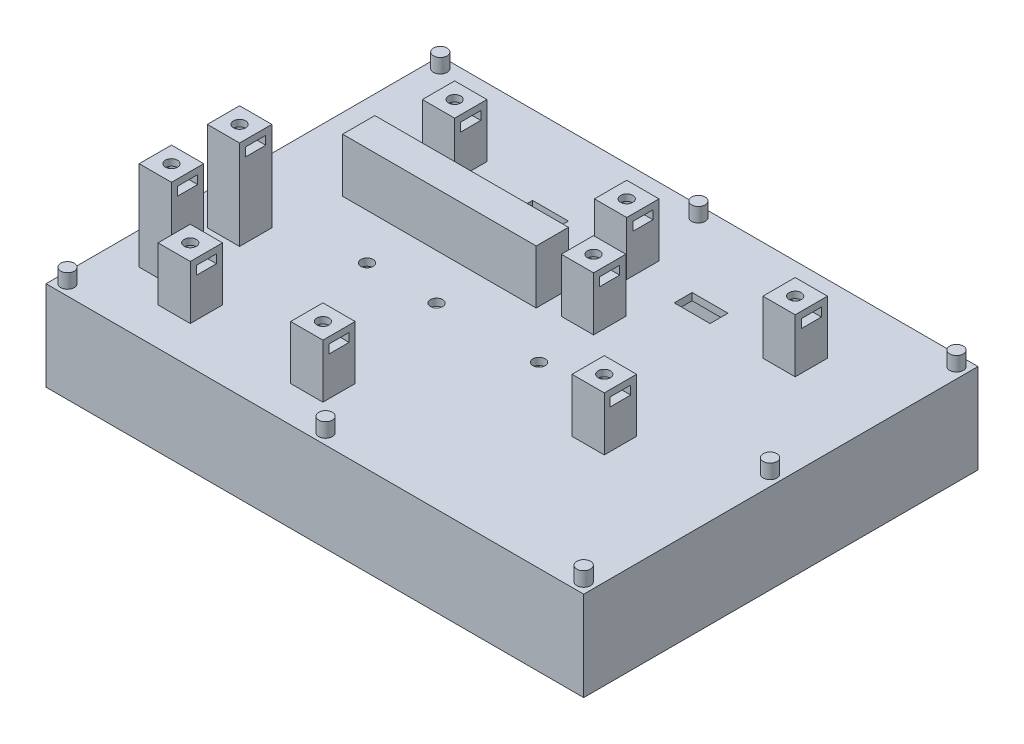
SolidWorks part; units mm, degrees
ref_plane "Front Plane" through (0, 0, 0) normal (0, 0, 1) x (1, 0, 0)
ref_plane "Top Plane" through (0, 0, 0) normal (0, 1, 0) x (1, 0, 0)
ref_plane "Right Plane" through (0, 0, 0) normal (1, 0, 0) x (0, 0, -1)
sketch "Sketch1" plane through (0, 0, 0) normal (0, 1, 0) x (1, 0, 0)
  line L1 (0, 0) -> (150, 0)
  line L2 (0, 0) -> (0, 110)
  line L3 (0, 110) -> (150, 110)
  line L4 (150, 0) -> (150, 110)
  dimension "D1" = 150
  dimension "D2" = 110
extrude "Boss-Extrude1" add sketch "Sketch1" along normal blind 25
sketch "PCB" plane through (0, 25, 0) normal (0, 1, 0) x (1, 0, 0)
  line L1 (20.25, 72) -> (129.75, 72)
  line L2 (20.25, 72) -> (20.25, 9.5)
  line L3 (20.25, 9.5) -> (129.75, 9.5)
  line L4 (129.75, 72) -> (129.75, 9.5)
  line L5 (0, 0) -> (150, 0) construction
  line L6 (150, 0) -> (150, 110) construction
  line L7 (0, 110) -> (0, 0) construction
  line L8 (150, 110) -> (0, 110) construction
  line L9 (24.5, 100.5) -> (125.5, 100.5)
  line L10 (24.5, 100.5) -> (24.5, 74)
  line L11 (24.5, 74) -> (125.5, 74)
  line L12 (125.5, 100.5) -> (125.5, 74)
  point P16 (75, 72)
  point P17 (75, 74)
  dimension "D1" = 109.5
  dimension "D2" = 62.5
  dimension "D3" = 9.5
  dimension "D4" = 20.25
  dimension "D5" = 20.25
  dimension "D6" = 26.5
  dimension "D7" = 2
  dimension "D8" = 9.5
  dimension "D9" = 101
sketch "Sketch10" plane through (0, 0, 0) normal (0, -1, 0) x (1, 0, 0)
  line L0 (0, 0) -> (150, 0) construction
  line L1 (117.75, -90) -> (32.25, -90)
  line L2 (117.75, -90) -> (117.75, -12)
  line L3 (117.75, -12) -> (32.25, -12)
  line L4 (32.25, -90) -> (32.25, -12)
  line L6 (150, -110) -> (0, -110) construction
  line L7 (150, 0) -> (150, -110) construction
  dimension "D1" = 85.5
  dimension "D2" = 78
  dimension "D3" = 20
  dimension "D4" = 32.25
  dimension "D5" = 12
sketch "Sketch27" plane through (0, 25, 0) normal (0, 1, 0) x (1, 0, 0)
  line L0 (150, 110) -> (0, 110) construction
  line L1 (0, 110) -> (0, 0) construction
  line L2 (0, 0) -> (150, 0) construction
  line L3 (150, 0) -> (150, 110) construction
  circle A0 centre (3, 107) radius 1.9
  circle A1 centre (75, 107) radius 1.9
  circle A2 centre (147, 107) radius 1.9
  circle A3 centre (147, 55) radius 1.9
  circle A4 centre (147, 3) radius 1.9
  circle A5 centre (75, 3) radius 1.9
  circle A6 centre (3, 3) radius 1.9
  circle A7 centre (3, 55) radius 1.9
  point P21 (0, 55)
  point P26 (75, 0)
  point P32 (150, 55)
  point P35 (75, 110)
  dimension "D1" = 3.8
  dimension "D4" = 3.8
  dimension "D5" = 3.8
  dimension "D6" = 3.8
  dimension "D7" = 3.8
  dimension "D8" = 3.8
  dimension "D9" = 3.8
  dimension "D10" = 3.8
  dimension "D2" = 3
  dimension "D3" = 3
  dimension "D11" = 3
  dimension "D12" = 3
  dimension "D13" = 3
  dimension "D14" = 3
extrude "Connectors" add sketch "Sketch27" along normal blind 4
sketch "Sketch31" plane through (0, 25, 0) normal (0, 1, 0) x (1, 0, 0)
  line L0 (24.5, 100.5) -> (24.5, 74) construction
  line L1 (118, 91) -> (127, 91)
  line L2 (118, 91) -> (118, 82)
  line L3 (129.75, 41) -> (114.75, 41) construction
  line L6 (20.25, 72) -> (20.25, 9.5) construction
  line L7 (20.25, 15) -> (25.25, 15) construction
  line L9 (84.25, 72) -> (84.25, 68.5) construction
  line L10 (129.75, 72) -> (129.75, 9.5) construction
  line L11 (20.25, 72) -> (129.75, 72) construction
  line L12 (118, 82) -> (127, 82)
  line L13 (20.25, 9.5) -> (129.75, 9.5) construction
  line L14 (127, 91) -> (127, 82)
  line L15 (20.75, 19.5) -> (29.75, 19.5)
  line L16 (20.75, 19.5) -> (20.75, 10.5)
  line L17 (20.75, 10.5) -> (29.75, 10.5)
  line L18 (29.75, 19.5) -> (29.75, 10.5)
  line L19 (20.75, 19.5) -> (29.75, 10.5) construction
  line L20 (20.75, 10.5) -> (29.75, 19.5) construction
  line L21 (58.25, 19) -> (67.25, 19)
  line L22 (58.25, 19) -> (58.25, 10)
  line L23 (58.25, 10) -> (67.25, 10)
  line L24 (67.25, 19) -> (67.25, 10)
  line L25 (58.25, 19) -> (67.25, 10) construction
  line L26 (58.25, 10) -> (67.25, 19) construction
  line L27 (110.25, 45.5) -> (119.25, 45.5)
  line L28 (110.25, 45.5) -> (110.25, 36.5)
  line L29 (110.25, 36.5) -> (119.25, 36.5)
  line L30 (119.25, 45.5) -> (119.25, 36.5)
  line L31 (110.25, 45.5) -> (119.25, 36.5) construction
  line L32 (110.25, 36.5) -> (119.25, 45.5) construction
  line L33 (79.75, 73) -> (88.75, 73)
  line L34 (79.75, 73) -> (79.75, 64)
  line L35 (79.75, 64) -> (88.75, 64)
  line L36 (88.75, 73) -> (88.75, 64)
  line L37 (79.75, 73) -> (88.75, 64) construction
  line L38 (79.75, 64) -> (88.75, 73) construction
  line L43 (118, 91) -> (127, 82) construction
  line L44 (118, 82) -> (127, 91) construction
  line L49 (71, 91) -> (80, 91)
  line L50 (71, 91) -> (71, 82)
  line L51 (71, 82) -> (80, 82)
  line L52 (80, 91) -> (80, 82)
  line L53 (71, 91) -> (80, 82) construction
  line L54 (71, 82) -> (80, 91) construction
  line L55 (23, 91) -> (32, 91)
  line L56 (23, 91) -> (23, 82)
  line L57 (23, 82) -> (32, 82)
  line L58 (32, 91) -> (32, 82)
  line L59 (23, 91) -> (32, 82) construction
  line L60 (23, 82) -> (32, 91) construction
  line L61 (24.5, 74) -> (125.5, 74) construction
  line L62 (125.5, 100.5) -> (125.5, 74) construction
  line L63 (150, 110) -> (0, 110) construction
  point P0 (122.5, 86.5)
  point P8 (75.5, 86.5)
  point P40 (27.5, 86.5)
  point P48 (62.75, 14.5)
  dimension "D3" = 5
  dimension "D4" = 37.5
  dimension "D5" = 5.5
  dimension "D6" = 45.5
  dimension "D7" = 3.5
  dimension "D8" = 15
  dimension "D9" = 31.5
  dimension "D10" = 9
  dimension "D11" = 9
  dimension "D12" = 9
  dimension "D13" = 9
  dimension "D14" = 9
  dimension "D15" = 9
  dimension "D16" = 9
  dimension "D17" = 9
  dimension "D18" = 9
  dimension "D19" = 9
  dimension "D20" = 9
  dimension "D21" = 9
  dimension "D22" = 5
  dimension "D23" = 9
  dimension "D24" = 9
  dimension "D25" = 3
  dimension "D26" = 12.5
  dimension "D27" = 12.5
  dimension "D28" = 50
  dimension "D29" = 3
  dimension "D30" = 12.5
  dimension "D31" = 23.5
extrude "Pillars" add sketch "Sketch31" along normal blind 15
hole_wizard "M3 Clearance Hole3" positions "3DSketch1" profile "Sketch32" hole size "M3" standard "ANSI Metric"
sketch3d "3DSketch1"
  line L0 (58.25, 40, -10) -> (67.25, 40, -10) construction
  point P4 (84.25, 40, -68.5)
  point P6 (114.75, 40, -41)
  point P8 (62.75, 40, -14.5)
  point P10 (25.25, 40, -15)
  point P56 (27.5, 40, -86.5)
  point P58 (75.5, 40, -86.5)
  point P60 (122.5, 40, -86.5)
  dimension "D1" = 4.5
sketch "Sketch32" plane through (84.25, 40, -68.5) normal (1, 0, 0) x (0, 0, 1)
  line L0 (0, 0) -> (0, 6.0215)
  line L1 (0, 6.0215) -> (1.7, 5)
  line L2 (1.7, 5) -> (1.7, 0)
  line L5 (1.7, 0) -> (0, 0)
  line L10 (0, 6.0215) -> (-1.7, 5) construction
  line L11 (0, -6.35) -> (0, 107.95) construction
  dimension "Hole Dia." = 3.4
  dimension "Hole Depth" = 5
  dimension "Drill Angle" = 118
sketch "Sketch33" plane through (119.25, 0, 0) normal (1, 0, 0) x (0, 0, -1)
  line L0 (36.5, 40) -> (45.5, 40) construction
  line L1 (38.15, 38.2) -> (43.85, 38.2)
  line L2 (38.15, 38.2) -> (38.15, 35.8)
  line L3 (38.15, 35.8) -> (43.85, 35.8)
  line L4 (43.85, 38.2) -> (43.85, 35.8)
  line L5 (38.15, 38.2) -> (43.85, 35.8) construction
  line L6 (38.15, 35.8) -> (43.85, 38.2) construction
  point P0 (41, 37)
  point P8 (41, 40)
  dimension "D1" = 5.7
  dimension "D2" = 2.4
  dimension "D3" = 1.8
extrude "Nut1" cut sketch "Sketch33" against normal blind 10
sketch "Sketch34" plane through (88.75, 0, 0) normal (1, 0, 0) x (0, 0, -1)
  line L0 (64, 40) -> (73, 40) construction
  line L1 (65.7, 38.2) -> (71.3, 38.2)
  line L2 (65.7, 38.2) -> (65.7, 35.8)
  line L3 (65.7, 35.8) -> (71.3, 35.8)
  line L4 (71.3, 38.2) -> (71.3, 35.8)
  line L5 (65.7, 38.2) -> (71.3, 35.8) construction
  line L6 (65.7, 35.8) -> (71.3, 38.2) construction
  point P0 (68.5, 37)
  point P8 (68.5, 40)
  dimension "D1" = 1.8
  dimension "D2" = 2.4
  dimension "D3" = 5.6
extrude "Nut2" cut sketch "Sketch34" against normal blind 10
sketch "Sketch37" plane through (67.25, 0, 0) normal (1, 0, 0) x (0, 0, -1)
  line L0 (10, 40) -> (19, 40) construction
  line L1 (11.7, 38.2) -> (17.3, 38.2)
  line L2 (11.7, 38.2) -> (11.7, 35.8)
  line L3 (11.7, 35.8) -> (17.3, 35.8)
  line L4 (17.3, 38.2) -> (17.3, 35.8)
  line L5 (11.7, 38.2) -> (17.3, 35.8) construction
  line L6 (11.7, 35.8) -> (17.3, 38.2) construction
  point P0 (14.5, 37)
  point P8 (14.5, 40)
  dimension "D1" = 2.4
  dimension "D2" = 5.6
  dimension "D3" = 1.8
extrude "Nut5" cut sketch "Sketch37" against normal blind 10
sketch "Sketch38" plane through (29.75, 0, 0) normal (1, 0, 0) x (0, 0, -1)
  line L0 (10.5, 40) -> (19.5, 40) construction
  line L1 (12.2, 38.2) -> (17.8, 38.2)
  line L2 (12.2, 38.2) -> (12.2, 35.8)
  line L3 (12.2, 35.8) -> (17.8, 35.8)
  line L4 (17.8, 38.2) -> (17.8, 35.8)
  line L5 (12.2, 38.2) -> (17.8, 35.8) construction
  line L6 (12.2, 35.8) -> (17.8, 38.2) construction
  point P0 (15, 37)
  point P8 (15, 40)
  dimension "D1" = 2.4
  dimension "D2" = 1.8
  dimension "D3" = 5.6
extrude "Nut6" cut sketch "Sketch38" against normal blind 10 contours L1 L4 L3 L2
extrude "Battery holder" cut sketch "Sketch10" against normal blind 23
sketch "Sketch39" plane through (0, 23, 0) normal (0, -1, 0) x (1, 0, 0)
  line L0 (117.75, -12) -> (32.25, -12) construction
  line L1 (76.75, -76) -> (69.75, -76)
  line L2 (76.75, -76) -> (76.75, -16)
  line L3 (76.75, -16) -> (69.75, -16)
  line L4 (69.75, -76) -> (69.75, -16)
  line L5 (76.75, -76) -> (69.75, -16) construction
  line L6 (76.75, -16) -> (69.75, -76) construction
  line L7 (32.25, -12) -> (32.25, -90) construction
  line L8 (117.75, -90) -> (117.75, -12) construction
  point P0 (73.25, -46)
  dimension "D1" = 41
  dimension "D2" = 60
  dimension "D3" = 34
  dimension "D4" = 41
extrude "Divider" add sketch "Sketch39" along normal blind 10
hole_wizard "M3 Clearance Hole4" positions "3DSketch2" profile "Sketch40" hole size "M3" standard "ANSI Metric"
sketch3d "3DSketch2"
  line L0 (117.75, 23, -90) -> (117.75, 23, -12) construction
  line L2 (117.75, 23, -12) -> (32.25, 23, -12) construction
  line L4 (69.75, 23, -16) -> (69.75, 23, -76) construction
  point P0 (107.15, 23, -49.8)
  point P2 (87.75, 23, -49.8)
  point P4 (59.15, 23, -49.8)
  point P6 (39.75, 23, -49.8)
  dimension "D1" = 19.4
  dimension "D2" = 10.6
  dimension "D3" = 37.8
  dimension "D4" = 10.6
  dimension "D5" = 19.4
sketch "Sketch40" plane through (107.15, 23, -49.8) normal (1, 0, 0) x (0, 0, -1)
  line L0 (0, 0) -> (0, 6.0215)
  line L1 (0, 6.0215) -> (1.7, 5)
  line L2 (1.7, 5) -> (1.7, 0)
  line L5 (1.7, 0) -> (0, 0)
  line L10 (0, 6.0215) -> (-1.7, 5) construction
  line L11 (0, -6.35) -> (0, 107.95) construction
  dimension "Hole Dia." = 3.4
  dimension "Hole Depth" = 5
  dimension "Drill Angle" = 118
sketch "Sketch41" plane through (0, 23, 0) normal (0, -1, 0) x (1, 0, 0)
  line L0 (117.75, -90) -> (117.75, -12) construction
  line L1 (102.25, -88) -> (92.25, -88)
  line L2 (102.25, -88) -> (102.25, -83)
  line L3 (102.25, -83) -> (92.25, -83)
  line L4 (92.25, -88) -> (92.25, -83)
  line L5 (102.25, -88) -> (92.25, -83) construction
  line L6 (102.25, -83) -> (92.25, -88) construction
  line L7 (57.75, -88) -> (47.75, -88)
  line L8 (57.75, -88) -> (57.75, -83)
  line L9 (57.75, -83) -> (47.75, -83)
  line L10 (47.75, -88) -> (47.75, -83)
  line L11 (57.75, -88) -> (47.75, -83) construction
  line L12 (57.75, -83) -> (47.75, -88) construction
  line L13 (32.25, -12) -> (32.25, -90) construction
  line L15 (117.75, -12) -> (32.25, -12) construction
  point P0 (97.25, -85.5)
  point P5 (52.75, -85.5)
  dimension "D1" = 5
  dimension "D2" = 5
  dimension "D3" = 10
  dimension "D4" = 10
  dimension "D5" = 20.5
  dimension "D6" = 20.5
  dimension "D7" = 71
  dimension "D8" = 71
extrude "Battery wire" cut sketch "Sketch41" against normal blind 2
sketch "Sketch42" plane through (0, 0, 0) normal (0, -1, 0) x (1, 0, 0)
  line L0 (32.25, -90) -> (117.75, -90) construction
  line L1 (117.75, -90) -> (117.75, -12) construction
  line L2 (32.25, -12) -> (32.25, -90) construction
  line L3 (117.75, -12) -> (32.25, -12) construction
  circle A0 centre (119.25, -10.5) radius 2
  circle A1 centre (30.75, -10.5) radius 2
  circle A2 centre (30.75, -91.5) radius 2
  circle A3 centre (119.25, -91.5) radius 2
  dimension "D1" = 4
  dimension "D4" = 4
  dimension "D9" = 4
  dimension "D12" = 4
  dimension "D2" = 1.5
  dimension "D3" = 1.5
  dimension "D5" = 1.5
  dimension "D6" = 1.5
  dimension "D7" = 1.5
  dimension "D8" = 1.5
  dimension "D10" = 1.5
  dimension "D11" = 1.5
  dimension "D13" = 88.5
  dimension "D14" = 81
  dimension "D15" = 88.5
  dimension "D16" = 81
extrude "Connector bottom" cut sketch "Sketch42" against normal blind 5
sketch "Sketch43" plane through (0, 25, 0) normal (0, 1, 0) x (1, 0, 0)
  line L0 (20.25, 72) -> (129.75, 72) construction
  line L1 (20.25, 71.5) -> (74.25, 71.5)
  line L2 (20.25, 71.5) -> (20.25, 62.5)
  line L3 (20.25, 62.5) -> (74.25, 62.5)
  line L4 (74.25, 71.5) -> (74.25, 62.5)
  line L9 (20.25, 72) -> (20.25, 9.5) construction
  dimension "D1" = 9
  dimension "D2" = 54
  dimension "D3" = 0
  dimension "D4" = 0.5
extrude "PCB rest" add sketch "Sketch43" along normal blind 15
sketch "Sketch44" plane through (127, 0, 0) normal (1, 0, 0) x (0, 0, -1)
  line L0 (82, 40) -> (91, 40) construction
  line L1 (89.3, 38.2) -> (83.7, 38.2)
  line L2 (89.3, 38.2) -> (89.3, 35.8)
  line L3 (89.3, 35.8) -> (83.7, 35.8)
  line L4 (83.7, 38.2) -> (83.7, 35.8)
  line L5 (89.3, 38.2) -> (83.7, 35.8) construction
  line L6 (89.3, 35.8) -> (83.7, 38.2) construction
  point P0 (86.5, 37)
  point P7 (86.5, 38.2)
  point P8 (86.5, 40)
  dimension "D1" = 2.4
  dimension "D2" = 5.6
  dimension "D3" = 1.8
extrude "Nut3" cut sketch "Sketch44" against normal blind 10
sketch "Sketch45" plane through (80, 0, 0) normal (1, 0, 0) x (0, 0, -1)
  line L0 (82, 40) -> (91, 40) construction
  line L1 (89.3, 38.2) -> (83.7, 38.2)
  line L2 (89.3, 38.2) -> (89.3, 35.8)
  line L3 (89.3, 35.8) -> (83.7, 35.8)
  line L4 (83.7, 38.2) -> (83.7, 35.8)
  line L5 (89.3, 38.2) -> (83.7, 35.8) construction
  line L6 (89.3, 35.8) -> (83.7, 38.2) construction
  point P0 (86.5, 37)
  point P7 (86.5, 38.2)
  point P8 (86.5, 40)
  dimension "D1" = 5.6
  dimension "D2" = 2.4
  dimension "D3" = 1.8
extrude "Nut4" cut sketch "Sketch45" against normal blind 10
sketch "Sketch46" plane through (32, 0, 0) normal (1, 0, 0) x (0, 0, -1)
  line L0 (82, 40) -> (91, 40) construction
  line L1 (83.7, 38.2) -> (89.3, 38.2)
  line L2 (83.7, 38.2) -> (83.7, 35.8)
  line L3 (83.7, 35.8) -> (89.3, 35.8)
  line L4 (89.3, 38.2) -> (89.3, 35.8)
  line L5 (83.7, 38.2) -> (89.3, 35.8) construction
  line L6 (83.7, 35.8) -> (89.3, 38.2) construction
  point P0 (86.5, 37)
  point P9 (86.5, 38.2)
  point P10 (86.5, 40)
  dimension "D1" = 5.6
  dimension "D2" = 2.4
  dimension "D3" = 1.8
extrude "Nut7" cut sketch "Sketch46" against normal blind 10
sketch "PCBInput" plane through (0, 25, 0) normal (0, 1, 0) x (1, 0, 0)
  line L0 (3, 31) -> (23, 31)
  line L1 (3, 43) -> (23, 43)
  line L2 (3, 43) -> (3, 19)
  line L3 (3, 19) -> (23, 19)
  line L4 (23, 43) -> (23, 19)
  line L5 (3, 43) -> (23, 19) construction
  line L6 (3, 19) -> (23, 43) construction
  line L7 (0, 110) -> (0, 0) construction
  line L8 (13.5, 43) -> (13.5, 40.5) construction
  line L9 (13.5, 19) -> (13.5, 21.5) construction
  line L10 (0, 0) -> (150, 0) construction
  point P0 (13, 31)
  dimension "D1" = 24
  dimension "D2" = 20
  dimension "D3" = 3
  dimension "D4" = 2.5
  dimension "D5" = 2.5
  dimension "D6" = 10.5
  dimension "D7" = 10.5
  dimension "D8" = 19
sketch "Sketch48" plane through (0, 25, 0) normal (0, 1, 0) x (1, 0, 0)
  line L1 (9, 45) -> (18, 45)
  line L2 (9, 45) -> (9, 36)
  line L3 (9, 36) -> (18, 36)
  line L4 (18, 45) -> (18, 36)
  line L5 (9, 45) -> (18, 36) construction
  line L6 (9, 36) -> (18, 45) construction
  line L7 (9, 26) -> (18, 26)
  line L8 (9, 26) -> (9, 17)
  line L9 (9, 17) -> (18, 17)
  line L10 (18, 26) -> (18, 17)
  line L11 (9, 26) -> (18, 17) construction
  line L12 (9, 17) -> (18, 26) construction
  point P0 (13.5, 40.5)
  point P6 (13.5, 21.5)
  dimension "D1" = 9
  dimension "D2" = 9
  dimension "D3" = 9
  dimension "D4" = 9
extrude "PCBInput pillars" add sketch "Sketch48" along normal blind 25 contours L3 L4 L1 L2
sketch "Sketch49" plane through (9, 0, 0) normal (-1, 0, 0) x (0, 0, 1)
  line L0 (-26, 50) -> (-17, 50) construction
  line L1 (-24.3, 45.8) -> (-18.7, 45.8)
  line L2 (-24.3, 45.8) -> (-24.3, 48.2)
  line L3 (-24.3, 48.2) -> (-18.7, 48.2)
  line L4 (-18.7, 45.8) -> (-18.7, 48.2)
  line L5 (-24.3, 45.8) -> (-18.7, 48.2) construction
  line L6 (-24.3, 48.2) -> (-18.7, 45.8) construction
  point P0 (-21.5, 47)
  point P7 (-21.5, 50)
  point P8 (-21.5, 48.2)
  dimension "D1" = 2.4
  dimension "D2" = 5.6
  dimension "D3" = 1.8
extrude "Nut8" cut sketch "Sketch49" against normal up to next
sketch "Sketch50" plane through (9, 0, 0) normal (-1, 0, 0) x (0, 0, 1)
  line L1 (-43.3, 45.8) -> (-37.7, 45.8)
  line L2 (-43.3, 45.8) -> (-43.3, 48.2)
  line L3 (-43.3, 48.2) -> (-37.7, 48.2)
  line L4 (-37.7, 45.8) -> (-37.7, 48.2)
  line L5 (-43.3, 45.8) -> (-37.7, 48.2) construction
  line L6 (-43.3, 48.2) -> (-37.7, 45.8) construction
  line L7 (-45, 50) -> (-36, 50) construction
  point P0 (-40.5, 47)
  point P7 (-40.5, 48.2)
  point P8 (-40.5, 50)
  dimension "D1" = 2.4
  dimension "D2" = 5.6
  dimension "D3" = 1.8
extrude "Nut9" cut sketch "Sketch50" against normal up to next
hole_wizard "M3 Clearance Hole5" positions "3DSketch3" profile "Sketch51" hole size "M3" standard "ANSI Metric"
sketch3d "3DSketch3"
  point P0 (13.5, 50, -40.5)
  point P2 (13.5, 50, -21.5)
sketch "Sketch51" plane through (13.5, 50, -40.5) normal (1, 0, 0) x (0, 0, 1)
  line L0 (0, 0) -> (0, 6.0215)
  line L1 (0, 6.0215) -> (1.7, 5)
  line L2 (1.7, 5) -> (1.7, 0)
  line L5 (1.7, 0) -> (0, 0)
  line L10 (0, 6.0215) -> (-1.7, 5) construction
  line L11 (0, -6.35) -> (0, 107.95) construction
  dimension "Hole Dia." = 3.4
  dimension "Hole Depth" = 5
  dimension "Drill Angle" = 118
